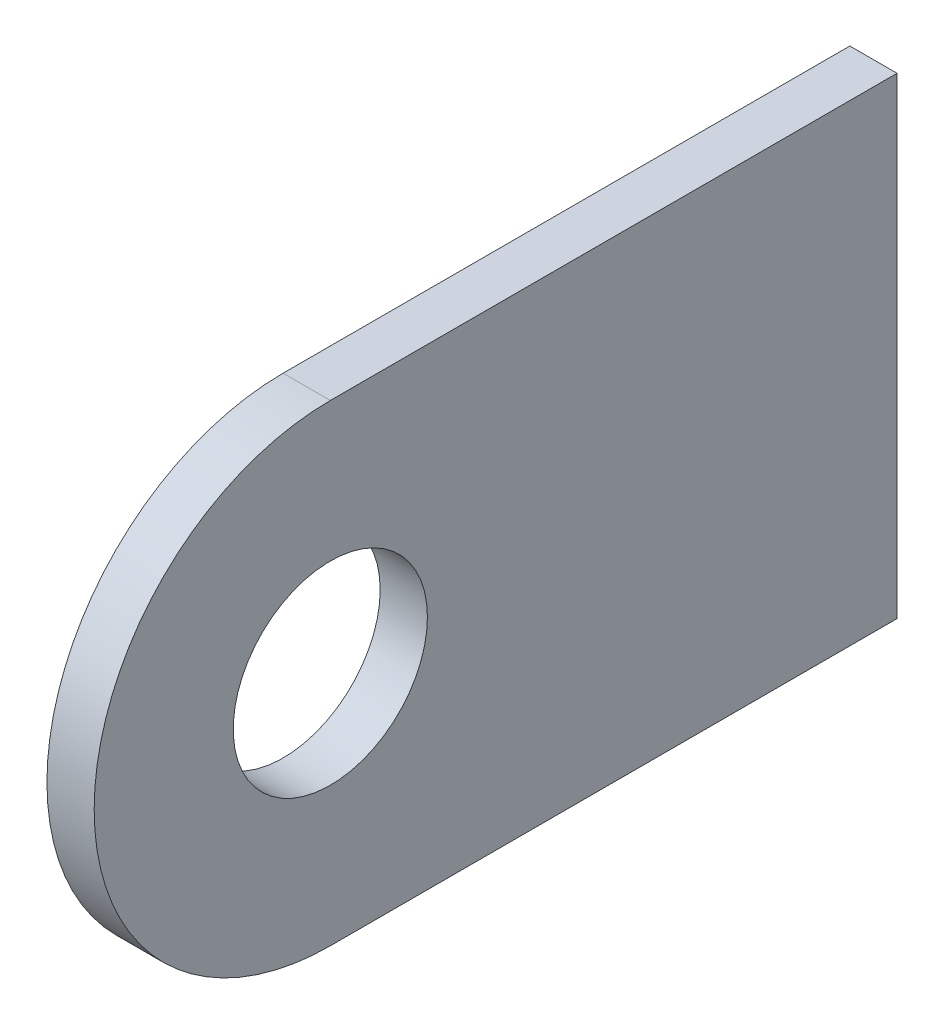
SolidWorks part; units mm, degrees
material "AISI 4130 Steel, annealed at 865C"
ref_plane "X-Y Datum" through (0, 0, 0) normal (0, 0, 1) x (1, 0, 0)
ref_plane "X-Z Datum" through (0, 0, 0) normal (0, 1, 0) x (1, 0, 0)
ref_plane "Y-Z Datum" through (0, 0, 0) normal (1, 0, 0) x (0, 0, -1)
sketch "Sketch1" plane through (0, 0, 0) normal (1, 0, 0) x (0, 0, -1)
  line L0 (0, -7.9375) -> (0, 7.9375)
  line L4 (-19.05, -7.9375) -> (0, -7.9375)
  line L5 (-19.05, 7.9375) -> (0, 7.9375)
  arc A1 (-19.05, -7.9375) -> (-19.05, 7.9375) centre (-19.05, 0) cw
  point P4 (0, 0)
  dimension "D1" = 19.05
  dimension "D2" = 7.9375
extrude "Boss-Extrude1" add sketch "Sketch1" along normal blind 1.5875
hole_wizard "1/4 Clearance Hole1" positions "Sketch2" profile "Sketch3" hole size "1/4" standard "ANSI Inch" end condition through all
sketch "Sketch2" plane through (1.5875, 0, 0) normal (1, 0, 0) x (0, 0, -1)
  point P0 (-19.05, 0)
sketch "Sketch3" plane through (1.5875, 0, 19.05) normal (0, 1, 0) x (0, 0, -1)
  line L0 (0, 0) -> (0, 1.5875)
  line L1 (0, 1.5875) -> (3.2639, 1.5875)
  line L2 (3.2639, 1.5875) -> (3.2639, 0)
  line L5 (3.2639, 0) -> (0, 0)
  line L11 (0, -6.35) -> (0, 107.95) construction
  dimension "Thru Hole Dia." = 6.5278
  dimension "Thru Hole Depth" = 1.5875
